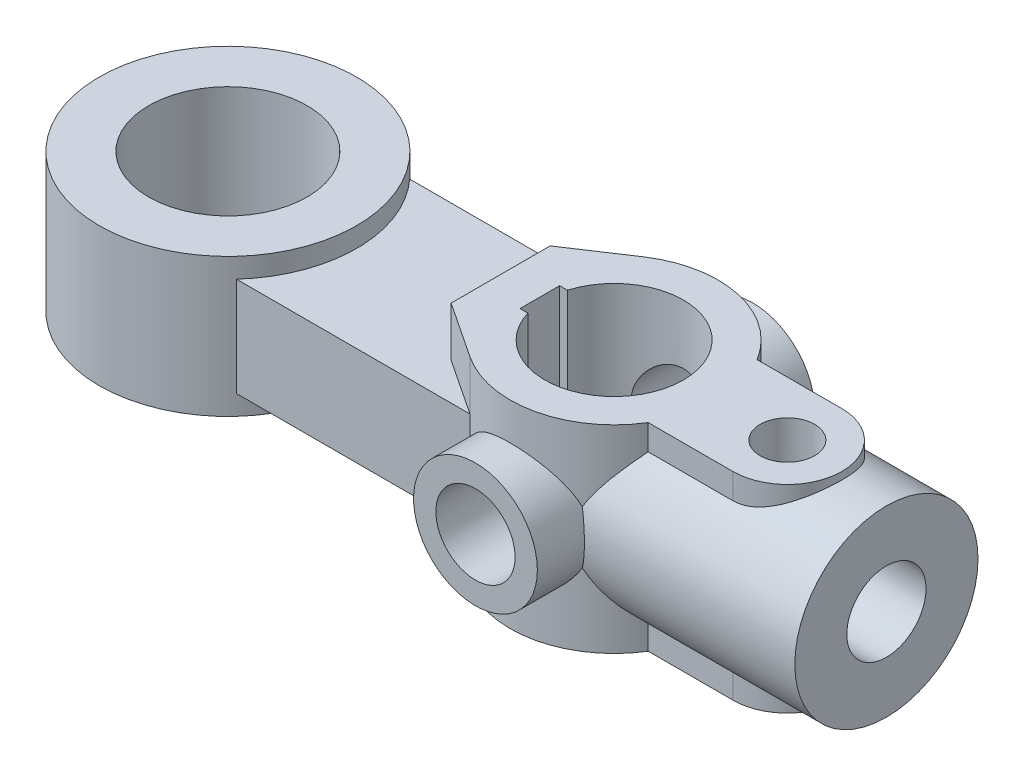
SolidWorks part; units mm, degrees
ref_plane "前视基准面" through (0, 0, 0) normal (0, 0, 1) x (1, 0, 0)
ref_plane "上视基准面" through (0, 0, 0) normal (0, 1, 0) x (1, 0, 0)
ref_plane "右视基准面" through (0, 0, 0) normal (1, 0, 0) x (0, 0, -1)
other "Configuration Table"
sketch "草图1" plane through (0, 0, 0) normal (0, 1, 0) x (1, 0, 0)
  line L0 (-5.8041, 8.75) -> (-11.4574, 5)
  line L1 (-11.4574, 5) -> (-11.4574, -5)
  line L2 (19.1345, 0) -> (-32.6542, 0) construction
  line L3 (-5.8041, -8.75) -> (-11.4574, -5)
  line L5 (8.9443, 5.5) -> (17.5, 5.5)
  line L7 (8.9443, -5.5) -> (17.5, -5.5)
  line L8 (17.5, 5.5) -> (17.5, -5.5)
  arc A0 (-5.8041, -8.75) -> (-5.8041, 8.75) centre (0, 0) ccw
  arc A1 (17.5, -5.5) -> (17.5, 5.5) centre (17.5, 0) ccw
  point P9 (-11.4574, 0)
  point P11 (10.5, 0)
  point P16 (0, 0)
  point P17 (0, 0)
  point P18 (-14.7025, -5)
  dimension "D1" = 21
  dimension "D3" = 11
  dimension "D4" = 17.5
  dimension "D2" = 10
  dimension "D5" = 17.5
extrude "凸台-拉伸1" add sketch "草图1" along normal mid plane 20
ref_plane "基准面1" through (27.5, 0, 0) normal (1, 0, 0) x (0, 0, -1)
sketch "草图2" plane through (27.5, 0, 0) normal (1, 0, 0) x (0, 0, -1)
  circle A0 centre (0, 0) radius 9.25
  dimension "D1" = 18.5
extrude "凸台-拉伸2" add sketch "草图2" against normal up to surface (22.5313 mm away)
sketch "草图3" plane through (27.5, 0, 0) normal (1, 0, 0) x (0, 0, -1)
  circle A0 centre (0, 0) radius 4
  dimension "D1" = 8
extrude "切除-拉伸1" cut sketch "草图3" against normal up to surface (17.7918 mm away)
sketch "草图4" plane through (0, 10, 0) normal (0, 1, 0) x (1, 0, 0)
  circle A0 centre (17.5, 0) radius 2.75
  dimension "D1" = 5.5
extrude "切除-拉伸2" cut sketch "草图4" against normal up to surface (20 mm away)
sketch "草图5" plane through (0, 0, 0) normal (0, 1, 0) x (1, 0, 0)
  line L0 (-5.8041, 8.75) -> (-11.4574, 5) construction
  line L1 (-11.4574, 5) -> (-11.4574, -5) construction
  line L2 (-5.8041, -8.75) -> (-11.4574, -5) construction
  line L3 (-5.8041, 8.75) -> (-11.4574, 5)
  line L4 (-11.4574, 5) -> (-11.4574, -5)
  line L5 (-5.8041, -8.75) -> (-11.4574, -5)
  line L6 (-5.8041, 8.75) -> (-39, 8.75)
  line L7 (-39, 8.75) -> (-39, -8.75)
  line L8 (-39, -8.75) -> (-5.8041, -8.75)
  dimension "D1" = 39
extrude "凸台-拉伸3" add sketch "草图5" along normal mid plane 10
sketch "草图6" plane through (0, 0, 0) normal (0, 1, 0) x (1, 0, 0)
  line L0 (-39, 8.75) -> (-39, -8.75) construction
  circle A0 centre (-39, 0) radius 13
  dimension "D1" = 26
extrude "凸台-拉伸4" add sketch "草图6" along normal mid plane 14
sketch "草图7" plane through (0, 7, 0) normal (0, 1, 0) x (1, 0, 0)
  circle A0 centre (-39, 0) radius 8
  dimension "D1" = 16
extrude "切除-拉伸3" cut sketch "草图7" against normal up to surface (14 mm away) up to face at (-39, -7, 13)
sketch "草图9" plane through (0, 10, 0) normal (0, 1, 0) x (1, 0, 0)
  line L5 (-7.4982, 2) -> (-6.7082, 2)
  line L6 (-7.4982, 2) -> (-7.4982, -2)
  line L7 (-7.4982, -2) -> (-6.7082, -2)
  circle A0 centre (0, 0) radius 7
  point P3 (0, 0)
  point P4 (-5.2181, 0)
  point P7 (0, 0)
  point P9 (-7.4982, 0)
  point P12 (-6.7082, -2)
  dimension "D1" = 14
  dimension "D2" = 4
  dimension "D3" = 0.79
extrude "切除-拉伸4" cut sketch "草图9" against normal up to surface (20 mm away) contours A0 L5 L6 L7 | A0
ref_plane "基准面3" through (0, 0, 14) normal (0, 0, 1) x (1, 0, 0)
sketch "草图11" plane through (0, 0, 14) normal (0, 0, 1) x (1, 0, 0)
  circle A0 centre (0, 0) radius 6.25
  dimension "D1" = 12.5
extrude "凸台-拉伸5" add sketch "草图11" against normal up to next
mirror "镜向1" about plane through (0, 0, 0) normal (0, 0, 1) of "凸台-拉伸5"
sketch "草图12" plane through (0, 0, 14) normal (0, 0, 1) x (1, 0, 0)
  circle A0 centre (0, 0) radius 4
  dimension "D1" = 8
extrude "切除-拉伸5" cut sketch "草图12" against normal up to surface (28 mm away) up to face at (6.25, 0, -14)
